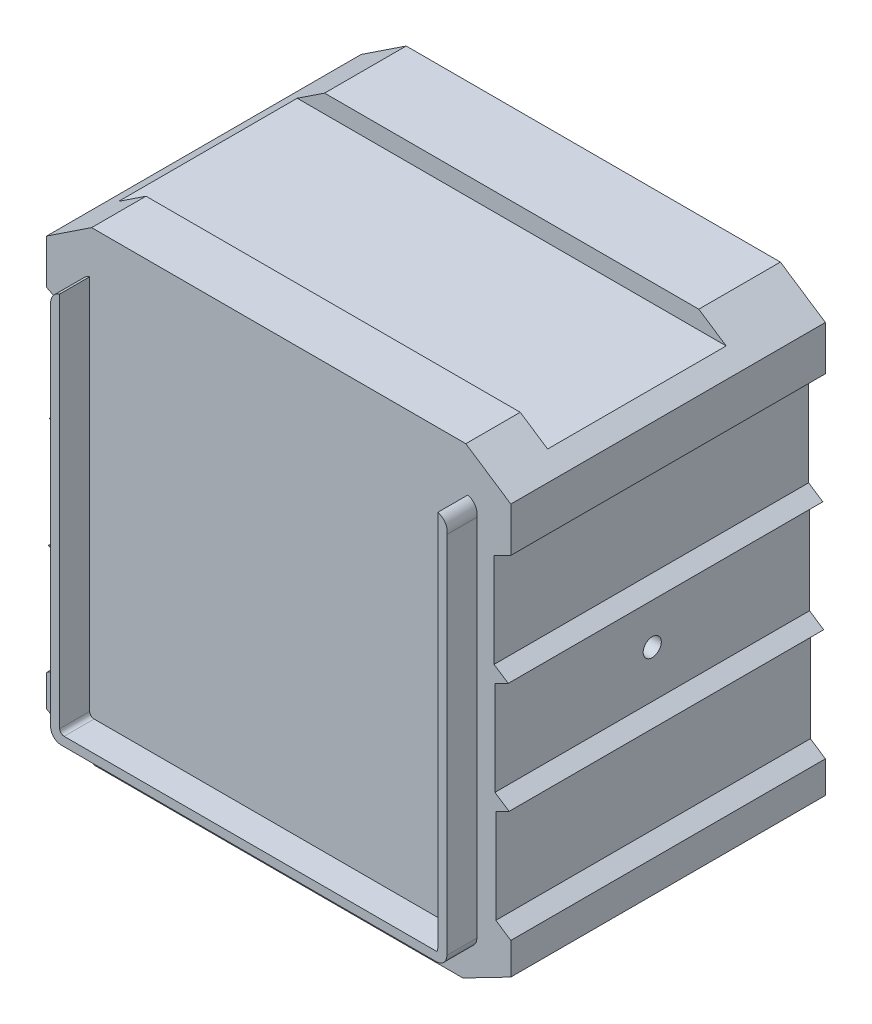
SolidWorks part; units mm, degrees
material "1060 Alloy"
ref_plane "Front" through (0, 0, 0) normal (0, 0, 1) x (1, 0, 0)
ref_plane "Top" through (0, 0, 0) normal (0, 1, 0) x (1, 0, 0)
ref_plane "Right" through (0, 0, 0) normal (1, 0, 0) x (0, 0, -1)
sketch "Sketch1" plane through (0, 0, 0) normal (0, 0, 1) x (1, 0, 0)
  line L0 (-103.1895, 0) -> (103.1895, 0)
  line L1 (103.1895, 0) -> (128, -16.4326)
  line L2 (128, -16.4326) -> (128, -40.963)
  line L3 (128, -40.963) -> (118.7742, -45.6193)
  line L4 (118.7742, -45.6193) -> (118.7742, -97.6193)
  line L5 (118.7742, -97.6193) -> (126.5833, -102.7916)
  line L6 (126.5833, -102.7916) -> (119.254, -106.4908)
  line L7 (119.254, -106.4908) -> (119.254, -158.4908)
  line L8 (119.254, -158.4908) -> (127.0632, -163.663)
  line L9 (127.0632, -163.663) -> (119.7339, -167.3622)
  line L10 (119.7339, -167.3622) -> (119.7339, -219.3622)
  line L11 (119.7339, -219.3622) -> (128, -224.837)
  line L12 (128, -224.837) -> (128, -242.3453)
  line L13 (128, -242.3453) -> (101.5588, -256)
  line L14 (101.5588, -256) -> (-101.5588, -256)
  line L15 (0, 0) -> (0, -256) construction
  line L16 (-128, -242.3453) -> (-101.5588, -256)
  line L17 (-128, -224.837) -> (-128, -242.3453)
  line L18 (-119.7339, -219.3622) -> (-128, -224.837)
  line L19 (-119.7339, -167.3622) -> (-119.7339, -219.3622)
  line L20 (-127.0632, -163.663) -> (-119.7339, -167.3622)
  line L21 (-119.254, -158.4908) -> (-127.0632, -163.663)
  line L22 (-119.254, -106.4908) -> (-119.254, -158.4908)
  line L23 (-126.5833, -102.7916) -> (-119.254, -106.4908)
  line L24 (-118.7742, -97.6193) -> (-126.5833, -102.7916)
  line L25 (-118.7742, -45.6193) -> (-118.7742, -97.6193)
  line L26 (-128, -40.963) -> (-118.7742, -45.6193)
  line L27 (-128, -16.4326) -> (-128, -40.963)
  line L28 (-103.1895, 0) -> (-128, -16.4326)
  dimension "D1" = 256
  dimension "D2" = 52
  dimension "D3" = 52
  dimension "D4" = 52
  dimension "D5" = 256
extrude "Boss-Extrude1" add sketch "Sketch1" along normal blind 173.478
sketch "Sketch3" plane through (0, 0, 173.478) normal (0, 0, 1) x (1, 0, 0)
  line L0 (-109.254, -30.7764) -> (-109.254, -233.135)
  line L1 (-103.389, -239) -> (103.389, -239)
  line L2 (109.254, -233.135) -> (109.254, -32.174)
  line L3 (104.254, -23.9952) -> (104.254, -231.7845)
  line L4 (103.7898, -234) -> (-101.83, -234)
  line L5 (-104.254, -231.576) -> (-104.254, -23.9952)
  line L6 (119.254, -158.4908) -> (119.254, -106.4908) construction
  line L7 (-119.254, -106.4908) -> (-119.254, -158.4908) construction
  line L8 (-101.5588, -256) -> (101.5588, -256) construction
  arc A0 (-109.254, -233.135) -> (-103.389, -239) centre (-103.389, -233.135) ccw
  arc A1 (103.389, -239) -> (109.254, -233.135) centre (103.389, -233.135) ccw
  arc A3 (104.254, -231.7845) -> (103.7898, -234) centre (98.7346, -231.7845) cw
  arc A4 (-101.83, -234) -> (-104.254, -231.576) centre (-101.83, -231.576) cw
  arc A5 (-109.254, -30.7764) -> (-104.254, -23.9952) centre (-102.1556, -30.7764) cw
  arc A6 (109.254, -32.174) -> (104.254, -23.9952) centre (102.6646, -30.5846) ccw
  dimension "D1" = 10
  dimension "D2" = 10
  dimension "D3" = 5
  dimension "D4" = 5
  dimension "D5" = 5
  dimension "D6" = 17
extrude "Boss-Extrude2" add sketch "Sketch3" along normal blind 16.522
sketch "Sketch5" plane through (0, 0, 0) normal (0, 1, 0) x (1, 0, 0)
  line L0 (-128, -173.478) -> (-128, 0) construction
  line L1 (-128, -143.478) -> (128, -143.478)
  line L2 (-128, -143.478) -> (-128, -45)
  line L3 (-128, -45) -> (128, -45)
  line L4 (128, -143.478) -> (128, -45)
  line L5 (128, -173.478) -> (128, 0) construction
  line L7 (103.7898, -173.478) -> (-101.83, -173.478) construction
  line L8 (103.1895, 0) -> (-103.1895, 0) construction
  dimension "D1" = 30
  dimension "D2" = 45
extrude "Cut-Extrude3" cut sketch "Sketch5" against normal blind 10
sketch "Sketch6" plane through (0, 0, 173.478) normal (0, 0, 1) x (1, 0, 0)
  line L0 (-17.4423, -269.8438) -> (292.5577, -269.8438) construction
sketch "Sketch7" plane through (119.254, 0, 0) normal (1, 0, 0) x (0, 0, -1)
  line L0 (-86.739, -106.4908) -> (-86.739, -158.4908)
  line L5 (-173.478, -106.4908) -> (0, -106.4908) construction
  line L6 (-173.478, -158.4908) -> (0, -158.4908) construction
  circle A0 centre (-86.739, -132.4908) radius 5
  point P8 (-86.739, -132.4908)
  dimension "D1" = 10
extrude "Cut-Extrude4" cut sketch "Sketch7" against normal through all contours A0
